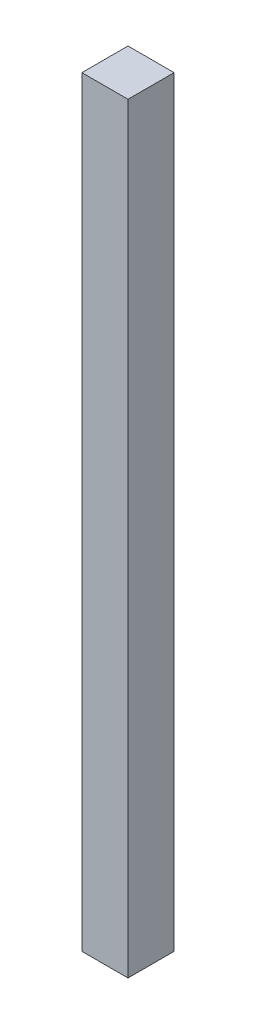
SolidWorks part; units mm, degrees
ref_plane "Front Plane" through (0, 0, 0) normal (0, 0, 1) x (1, 0, 0)
ref_plane "Top Plane" through (0, 0, 0) normal (0, 1, 0) x (1, 0, 0)
ref_plane "Right Plane" through (0, 0, 0) normal (1, 0, 0) x (0, 0, -1)
sketch "Sketch1" plane through (0, 0, 0) normal (0, 1, 0) x (1, 0, 0)
  line L1 (-10, 10) -> (10, 10)
  line L2 (-10, 10) -> (-10, -10)
  line L3 (-10, -10) -> (10, -10)
  line L4 (10, 10) -> (10, -10)
  line L5 (-10, 10) -> (10, -10) construction
  line L6 (-10, -10) -> (10, 10) construction
  point P0 (0, 0)
  dimension "D1" = 20
  dimension "D2" = 20
extrude "Boss-Extrude1" add sketch "Sketch1" along normal blind 330
